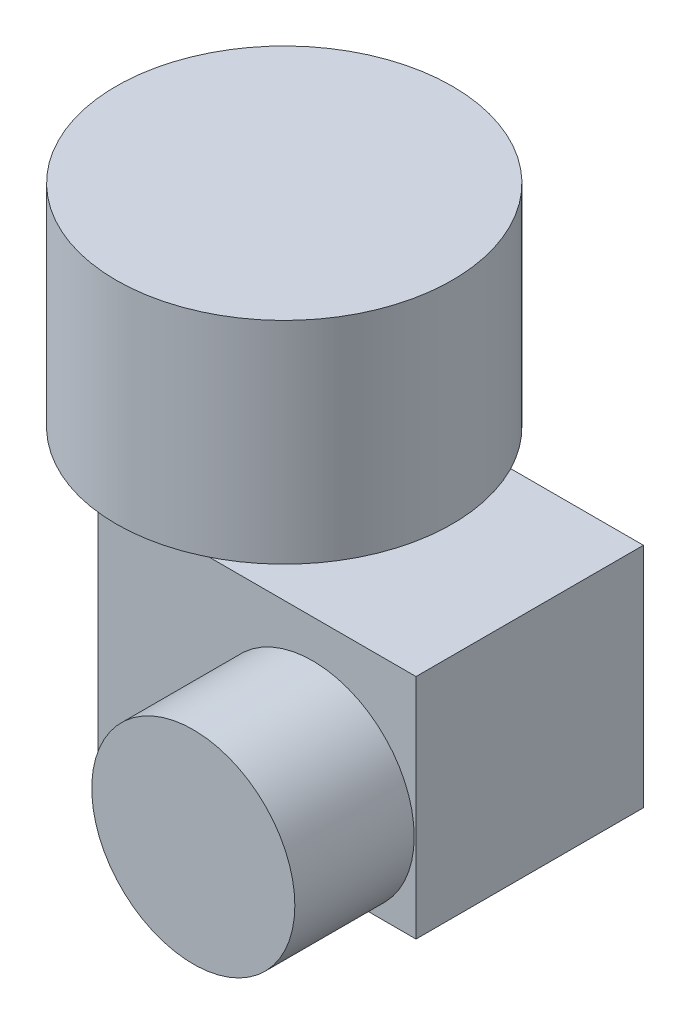
SolidWorks part; units mm, degrees
ref_plane "Front Plane" through (0, 0, 0) normal (0, 0, 1) x (1, 0, 0)
ref_plane "Top Plane" through (0, 0, 0) normal (0, 1, 0) x (1, 0, 0)
ref_plane "Right Plane" through (0, 0, 0) normal (1, 0, 0) x (0, 0, -1)
sketch "Sketch1" plane through (0, 0, 0) normal (1, 0, 0) x (0, 0, -1)
  line L1 (0, 0) -> (22.352, 0)
  line L2 (0, 0) -> (0, 22.352)
  line L3 (0, 22.352) -> (22.352, 22.352)
  line L4 (22.352, 0) -> (22.352, 22.352)
  dimension "D1" = 22.352
  dimension "D2" = 22.352
extrude "Boss-Extrude1" add sketch "Sketch1" against normal blind 31.242
sketch "Sketch2" plane through (0, 22.352, 0) normal (0, 1, 0) x (1, 0, 0)
  line L0 (-24.13, 22.352) -> (-24.13, 0) construction
  line L1 (-31.242, 22.352) -> (0, 22.352) construction
  line L2 (-31.242, 22.352) -> (-31.242, 0) construction
  line L3 (-31.242, 0) -> (0, 0) construction
  line L4 (0, 22.352) -> (0, 0) construction
  line L5 (-31.242, 11.176) -> (0, 11.176) construction
  circle A0 centre (-24.13, 11.176) radius 3.81
  dimension "D2" = 7.62
  dimension "D1" = 24.13
extrude "Boss-Extrude2" add sketch "Sketch2" along normal blind 1.0541
sketch "Sketch3" plane through (0, 23.4061, 0) normal (0, 1, 0) x (1, 0, 0)
  line L0 (-27.94, 11.176) -> (-20.32, 11.176) construction
  line L1 (-24.13, 14.986) -> (-24.13, 7.366) construction
  line L3 (-20.066, 7.112) -> (-28.194, 7.112)
  line L4 (-20.066, 7.112) -> (-20.066, 15.24)
  line L5 (-20.066, 15.24) -> (-28.194, 15.24)
  line L6 (-28.194, 7.112) -> (-28.194, 15.24)
  line L7 (-20.066, 7.112) -> (-28.194, 15.24) construction
  line L8 (-20.066, 15.24) -> (-28.194, 7.112) construction
  circle A0 centre (-24.13, 11.176) radius 3.81 construction
  circle A1 centre (-24.13, 11.176) radius 3.81 construction
  point P9 (-24.13, 11.176)
  dimension "D1" = 8.128
  dimension "D2" = 8.128
extrude "Boss-Extrude3" add sketch "Sketch3" along normal blind 2.54
sketch "Sketch4" plane through (0, 25.9461, 0) normal (0, 1, 0) x (1, 0, 0)
  line L0 (-24.13, 15.24) -> (-24.13, 7.112) construction
  line L1 (-20.066, 15.24) -> (-28.194, 15.24) construction
  line L2 (-28.194, 7.112) -> (-20.066, 7.112) construction
  line L3 (-28.194, 11.176) -> (-20.066, 11.176) construction
  line L4 (-28.194, 15.24) -> (-28.194, 7.112) construction
  line L5 (-20.066, 7.112) -> (-20.066, 15.24) construction
  circle A0 centre (-24.13, 11.176) radius 16.5227
  dimension "D1" = 33.0454
extrude "Boss-Extrude4" add sketch "Sketch4" along normal blind 20.7518
sketch "Sketch5" plane through (-31.242, 0, 0) normal (-1, 0, 0) x (0, 0, 1)
  line L0 (-11.176, 22.352) -> (-11.176, 0) construction
  line L1 (-22.352, 22.352) -> (0, 22.352) construction
  line L2 (0, 0) -> (-22.352, 0) construction
  line L3 (-22.352, 11.176) -> (0, 11.176) construction
  line L4 (-22.352, 0) -> (-22.352, 22.352) construction
  line L5 (0, 22.352) -> (0, 0) construction
  circle A0 centre (-11.176, 11.176) radius 3.81
  dimension "D1" = 7.62
extrude "Boss-Extrude5" add sketch "Sketch5" along normal blind 2.1082
sketch "Sketch6" plane through (0, 0, 0) normal (0, 0, 1) x (1, 0, 0)
  line L0 (-7.62, 22.352) -> (-7.62, 0) construction
  line L1 (-31.242, 22.352) -> (0, 22.352) construction
  line L2 (-31.242, 0) -> (0, 0) construction
  line L3 (-31.242, 11.176) -> (0, 11.176) construction
  line L4 (-31.242, 22.352) -> (-31.242, 0) construction
  line L5 (0, 22.352) -> (0, 0) construction
  circle A0 centre (-7.62, 11.176) radius 6.35
  dimension "D2" = 12.7
  dimension "D1" = 7.62
extrude "Boss-Extrude7" add sketch "Sketch6" along normal blind 2.54
sketch "Sketch7" plane through (0, 0, 2.54) normal (0, 0, 1) x (1, 0, 0)
  circle A0 centre (-7.62, 11.176) radius 9.9822
  dimension "D1" = 19.9644
extrude "Boss-Extrude8" add sketch "Sketch7" along normal blind 11.7348
